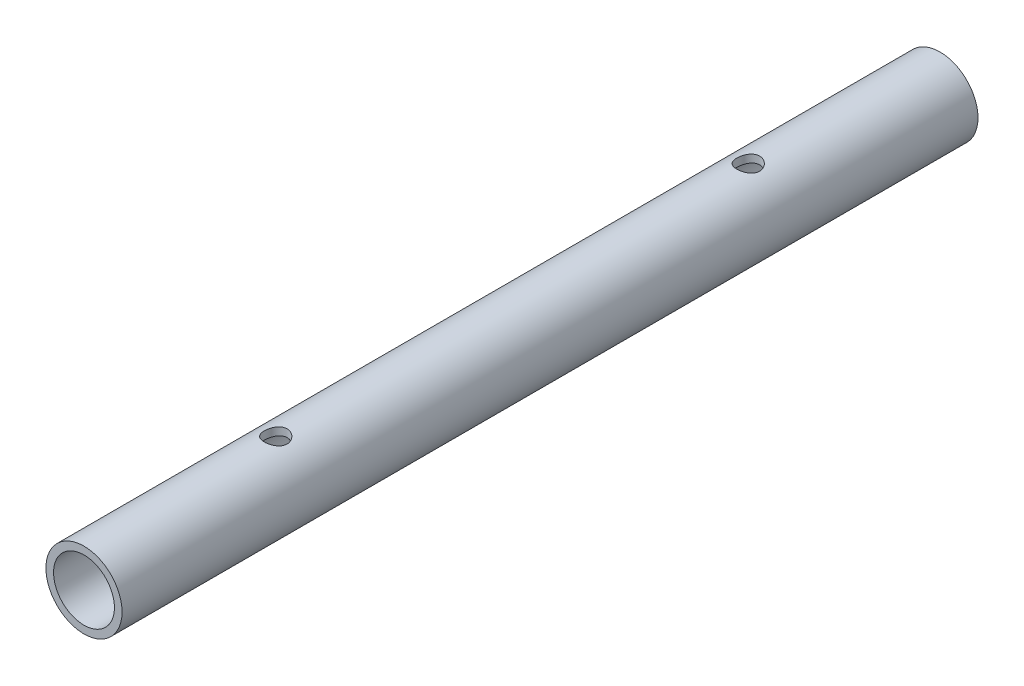
SolidWorks part; units mm, degrees
ref_plane "Plan de face" through (0, 0, 0) normal (0, 0, 1) x (1, 0, 0)
ref_plane "Plan de dessus" through (0, 0, 0) normal (0, 1, 0) x (1, 0, 0)
ref_plane "Plan de droite" through (0, 0, 0) normal (1, 0, 0) x (0, 0, -1)
sketch "Sketch1" plane through (0, 0, 0) normal (0, 0, 1) x (1, 0, 0)
  circle A0 centre (0, 0) radius 5
extrude "Boss-Extrude1" add sketch "Sketch1" along normal blind 112.46
sketch "Sketch2" plane through (0, 0, 112.46) normal (0, 0, 1) x (1, 0, 0)
  circle A0 centre (0, 0) radius 4
extrude "Cut-Extrude1" cut sketch "Sketch2" against normal up to next
sketch "Sketch5" plane through (0, 0, 0) normal (0, 1, 0) x (1, 0, 0)
  circle A0 centre (0, -25.191) radius 1.5
  circle A1 centre (0, -87.269) radius 1.5
  dimension "D1" = 25.191
  dimension "D2" = 87.269
extrude "Cut-Extrude2" cut sketch "Sketch5" against normal through all and the other way through all
